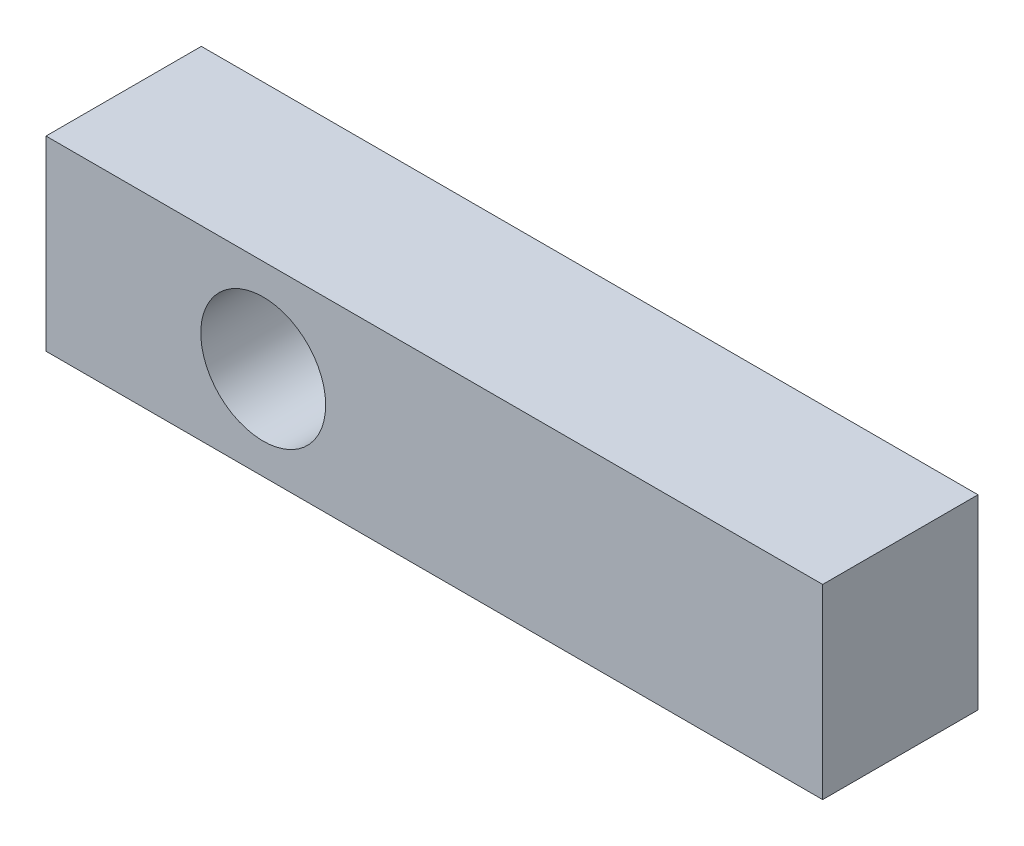
SolidWorks part; units mm, degrees
ref_plane "Front Plane" through (0, 0, 0) normal (0, 0, 1) x (1, 0, 0)
ref_plane "Top Plane" through (0, 0, 0) normal (0, 1, 0) x (1, 0, 0)
ref_plane "Right Plane" through (0, 0, 0) normal (1, 0, 0) x (0, 0, -1)
sketch "Sketch1" plane through (0, 0, 0) normal (0, 0, 1) x (1, 0, 0)
  line L1 (-12.5, -3) -> (12.5, -3)
  line L2 (-12.5, -3) -> (-12.5, 3)
  line L3 (-12.5, 3) -> (12.5, 3)
  line L4 (12.5, -3) -> (12.5, 3)
  line L5 (-12.5, -3) -> (12.5, 3) construction
  line L6 (-12.5, 3) -> (12.5, -3) construction
  point P0 (0, 0)
  dimension "D1" = 25
  dimension "D2" = 6
extrude "Boss-Extrude1" add sketch "Sketch1" along normal blind 5
sketch "Sketch2" plane through (0, 0, 5) normal (0, 0, 1) x (1, 0, 0)
  circle A0 centre (-5.5078, 0) radius 2.01
  point P2 (-5.5078, 0)
extrude "Cut-Extrude1" cut sketch "Sketch2" against normal blind 5
